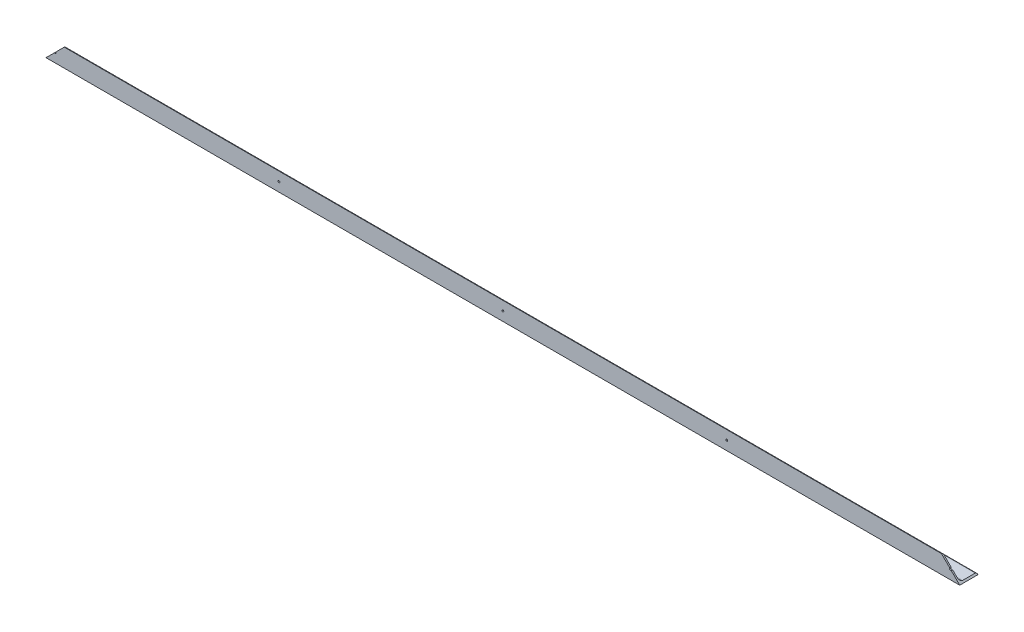
SolidWorks part; units mm, degrees
ref_plane "Front Plane" through (0, 0, 0) normal (0, 0, 1) x (1, 0, 0)
ref_plane "Top Plane" through (0, 0, 0) normal (0, 1, 0) x (1, 0, 0)
ref_plane "Right Plane" through (0, 0, 0) normal (1, 0, 0) x (0, 0, -1)
sketch "Sketch1" plane through (0, 0, 0) normal (0, 1, 0) x (1, 0, 0)
  line L0 (0, 0) -> (2000, 0)
  dimension "D1" = 2000
other "L angle (equal) 40X40X3(4)"
ref_plane "Plane1" through (0, 0, 0) normal (1, 0, 0) x (0, 0, -1)
sketch "Sketch13" plane through (0, 0, 0) normal (1, 0, 0) x (0, 0, -1)
  line L0 (0, 40) -> (0, 0)
  line L2 (3, 37) -> (3, 9)
  line L3 (9, 3) -> (37, 3)
  line L5 (40, 0) -> (0, 0)
  arc A0 (3, 37) -> (0, 40) centre (0, 37) ccw
  arc A1 (40, 0) -> (37, 3) centre (37, 0) ccw
  arc A2 (9, 3) -> (3, 9) centre (9, 9) cw
  point P8 (0, 20)
  point P9 (20, 0)
  point P10 (0, 0)
  dimension "Radius_2" = 3
  dimension "Radius_1" = 6
  dimension "V_leg" = 40
  dimension "H_leg" = 40
  dimension "thickness" = 3
sketch "Sketch14" plane through (0, 0, 0) normal (0, 0, 1) x (1, 0, 0)
  line L0 (2000, 0) -> (2000, 40)
  line L1 (0, 40) -> (0, 0)
  line L3 (1960, 40) -> (1978.5858, 21.4142)
  line L4 (0, 40) -> (0, 0)
  line L5 (0, 0) -> (2000, 0)
  line L6 (2000, 0) -> (2000, 40)
  line L7 (2000, 40) -> (0, 40)
  line L8 (0, 40) -> (0, 0) construction
  line L10 (2000, 0) -> (2000, 40) construction
  line L11 (2000, 40) -> (1960, 40)
  line L12 (40, 40) -> (0, 40)
  line L13 (1000, 40) -> (1000, 0) construction
  line L14 (2000, 40) -> (0, 40) construction
  line L15 (0, 0) -> (2000, 0) construction
  line L16 (1981.4142, 18.5858) -> (2000, 0)
  line L17 (0, 0) -> (18.5858, 18.5858)
  line L19 (21.4142, 21.4142) -> (40, 40)
  line L20 (1980, 18) -> (1980, 0) construction
  line L21 (510, 40) -> (510, 0) construction
  line L22 (1490, 40) -> (1490, 0) construction
  circle A0 centre (1000, 20) radius 2
  arc A1 (1978.5858, 21.4142) -> (1981.4142, 18.5858) centre (1980, 20) ccw
  arc A3 (18.5858, 18.5858) -> (21.4142, 21.4142) centre (20, 20) ccw
  circle A4 centre (510, 20) radius 2
  circle A5 centre (1490, 20) radius 2
  dimension "D2" = 40
  dimension "D5" = 40
  dimension "D1" = 0
extrude "Cut-Extrude1" cut sketch "Sketch14" against normal through all
